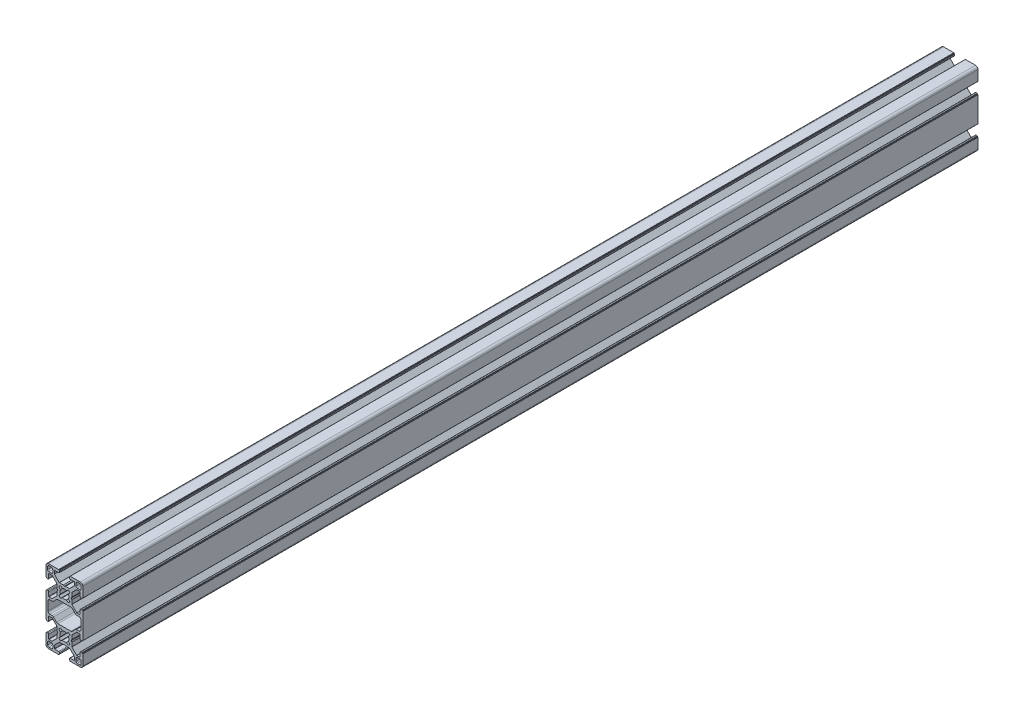
SolidWorks part; units mm, degrees
ref_plane "Front Plane" through (0, 0, 0) normal (0, 0, 1) x (1, 0, 0)
ref_plane "Top Plane" through (0, 0, 0) normal (0, 1, 0) x (1, 0, 0)
ref_plane "Right Plane" through (0, 0, 0) normal (1, 0, 0) x (0, 0, -1)
sketch "Sketch1" plane through (0, 0, 0) normal (0, 0, 1) x (1, 0, 0)
  line L0 (15.3348, -15) -> (-18.6959, -15) construction
  line L1 (-20.9994, 0) -> (26.1762, 0) construction
  line L2 (1.6001, -18.2806) -> (3.1547, -19.5053)
  line L3 (4.1172, -21) -> (0.9, -21)
  line L4 (4.35, -29.5) -> (4.25, -29.5)
  line L5 (4.05, -29.3) -> (4.05, -28.4)
  line L6 (4.55, -29.7) -> (4.55, -29.8)
  line L7 (0.9, -21) -> (0.1019, -20.5392)
  line L8 (1.6001, -11.7194) -> (3.1547, -10.4947)
  line L9 (3.2806, -13.3999) -> (4.5184, -11.8641)
  line L10 (3.2806, -16.6001) -> (4.5184, -18.1359)
  line L11 (6.0045, -19.1216) -> (6.0045, -15.9)
  line L12 (12.6, -23.25) -> (10.1328, -23.25)
  line L13 (10.5, -24.5) -> (12.7, -24.5)
  line L14 (12.7, -28.7) -> (10.5, -28.7)
  line L15 (15, -28) -> (15, -19.75)
  line L16 (13.7, -25.5) -> (13.7, -27.7)
  line L17 (14.8, -19.55) -> (14.7, -19.55)
  line L18 (14.5, -19.35) -> (14.5, -19.25)
  line L19 (14.3, -19.05) -> (13.4, -19.05)
  line L20 (12.8, -19.65) -> (12.8, -23.05)
  line L21 (8.25, -27.6) -> (8.25, -25.1328)
  line L22 (9.5, -27.7) -> (9.5, -25.5)
  line L23 (9.9914, -23.1914) -> (6.063, -19.263)
  line L24 (12.8, -10.35) -> (12.8, -6.95)
  line L25 (15, 10.25) -> (15, -10.25)
  line L26 (9.9914, -6.8086) -> (6.063, -10.737)
  line L27 (8.9272, -5.5393) -> (6.4104, -8.0562)
  line L28 (14.3, -10.95) -> (13.4, -10.95)
  line L29 (14.5, -10.65) -> (14.5, -10.75)
  line L30 (14.8, -10.45) -> (14.7, -10.45)
  line L31 (6.0045, -10.8784) -> (6.0045, -14.1)
  line L32 (6.0045, -15.9) -> (5.5426, -15.1)
  line L33 (6.0045, -14.1) -> (5.5426, -14.9)
  line L34 (12.6, -6.75) -> (10.1328, -6.75)
  line L35 (11.85, -5.1) -> (9.9879, -5.1)
  line L36 (13.35, 3.6) -> (13.35, -3.6)
  line L37 (4.75, -30) -> (13, -30)
  line L38 (8.1914, -24.9914) -> (4.2586, -21.0586)
  line L39 (4.65, -27.8) -> (8.05, -27.8)
  line L40 (-1.6001, 18.2806) -> (-3.1547, 19.5053)
  line L41 (-4.1172, 21) -> (-0.9, 21)
  line L42 (-4.35, 29.5) -> (-4.25, 29.5)
  line L43 (-4.05, 29.3) -> (-4.05, 28.4)
  line L44 (-4.55, 29.7) -> (-4.55, 29.8)
  line L45 (-0.9, 21) -> (-0.1019, 20.5392)
  line L46 (-1.6001, 11.7194) -> (-3.1547, 10.4947)
  line L47 (-5.3497, 8.4955) -> (5.3497, 8.4955)
  line L48 (-3.2806, 13.3999) -> (-4.5184, 11.8641)
  line L49 (-3.2806, 16.6001) -> (-4.5184, 18.1359)
  line L50 (-6.0045, 19.1216) -> (-6.0045, 15.9)
  line L51 (-12.6, 23.25) -> (-10.1328, 23.25)
  line L52 (-10.5, 24.5) -> (-12.7, 24.5)
  line L53 (-12.7, 28.7) -> (-10.5, 28.7)
  line L54 (-15, 28) -> (-15, 19.75)
  line L55 (-13.7, 25.5) -> (-13.7, 27.7)
  line L56 (-14.8, 19.55) -> (-14.7, 19.55)
  line L57 (-14.5, 19.35) -> (-14.5, 19.25)
  line L58 (-14.3, 19.05) -> (-13.4, 19.05)
  line L59 (-12.8, 19.65) -> (-12.8, 23.05)
  line L60 (-8.25, 27.6) -> (-8.25, 25.1328)
  line L61 (-9.5, 27.7) -> (-9.5, 25.5)
  line L62 (-9.9914, 23.1914) -> (-6.063, 19.263)
  line L63 (-12.8, 10.35) -> (-12.8, 6.95)
  line L64 (-9.9914, 6.8086) -> (-6.063, 10.737)
  line L65 (-8.9272, 5.5393) -> (-6.4104, 8.0562)
  line L66 (-14.3, 10.95) -> (-13.4, 10.95)
  line L67 (-14.5, 10.65) -> (-14.5, 10.75)
  line L68 (-14.8, 10.45) -> (-14.7, 10.45)
  line L69 (-6.0045, 10.8784) -> (-6.0045, 14.1)
  line L70 (-6.0045, 15.9) -> (-5.5426, 15.1)
  line L71 (-6.0045, 14.1) -> (-5.5426, 14.9)
  line L72 (-12.6, 6.75) -> (-10.1328, 6.75)
  line L73 (-11.85, 5.1) -> (-9.9879, 5.1)
  line L74 (-4.75, 30) -> (-13, 30)
  line L75 (-8.1914, 24.9914) -> (-4.2586, 21.0586)
  line L76 (-4.65, 27.8) -> (-8.05, 27.8)
  line L77 (4.65, 27.8) -> (8.05, 27.8)
  line L78 (8.1914, 24.9914) -> (4.2586, 21.0586)
  line L79 (4.75, 30) -> (13, 30)
  line L80 (11.85, 5.1) -> (9.9879, 5.1)
  line L81 (12.6, 6.75) -> (10.1328, 6.75)
  line L82 (6.0045, 14.1) -> (5.5426, 14.9)
  line L83 (6.0045, 15.9) -> (5.5426, 15.1)
  line L84 (6.0045, 10.8784) -> (6.0045, 14.1)
  line L85 (14.8, 10.45) -> (14.7, 10.45)
  line L86 (14.5, 10.65) -> (14.5, 10.75)
  line L87 (14.3, 10.95) -> (13.4, 10.95)
  line L88 (8.9272, 5.5393) -> (6.4104, 8.0562)
  line L89 (9.9914, 6.8086) -> (6.063, 10.737)
  line L90 (12.8, 10.35) -> (12.8, 6.95)
  line L91 (9.9914, 23.1914) -> (6.063, 19.263)
  line L92 (9.5, 27.7) -> (9.5, 25.5)
  line L93 (8.25, 27.6) -> (8.25, 25.1328)
  line L94 (12.8, 19.65) -> (12.8, 23.05)
  line L95 (14.3, 19.05) -> (13.4, 19.05)
  line L96 (14.5, 19.35) -> (14.5, 19.25)
  line L97 (14.8, 19.55) -> (14.7, 19.55)
  line L98 (13.7, 25.5) -> (13.7, 27.7)
  line L99 (15, 28) -> (15, 19.75)
  line L100 (12.7, 28.7) -> (10.5, 28.7)
  line L101 (10.5, 24.5) -> (12.7, 24.5)
  line L102 (12.6, 23.25) -> (10.1328, 23.25)
  line L103 (6.0045, 19.1216) -> (6.0045, 15.9)
  line L104 (3.2806, 16.6001) -> (4.5184, 18.1359)
  line L105 (3.2806, 13.3999) -> (4.5184, 11.8641)
  line L106 (1.6001, 11.7194) -> (3.1547, 10.4947)
  line L107 (0.9, 21) -> (0.1019, 20.5392)
  line L108 (4.55, 29.7) -> (4.55, 29.8)
  line L109 (4.05, 29.3) -> (4.05, 28.4)
  line L110 (4.35, 29.5) -> (4.25, 29.5)
  line L111 (4.1172, 21) -> (0.9, 21)
  line L112 (1.6001, 18.2806) -> (3.1547, 19.5053)
  line L155 (0, 26.7355) -> (0, -34.1789) construction
  line L156 (-4.65, -27.8) -> (-8.05, -27.8)
  line L157 (-8.1914, -24.9914) -> (-4.2586, -21.0586)
  line L158 (-4.75, -30) -> (-13, -30)
  line L162 (-13.35, 3.6) -> (-13.35, -3.6)
  line L163 (-11.85, -5.1) -> (-9.9879, -5.1)
  line L164 (-12.6, -6.75) -> (-10.1328, -6.75)
  line L165 (-6.0045, -14.1) -> (-5.5426, -14.9)
  line L166 (-6.0045, -15.9) -> (-5.5426, -15.1)
  line L167 (-6.0045, -10.8784) -> (-6.0045, -14.1)
  line L168 (-14.8, -10.45) -> (-14.7, -10.45)
  line L169 (-14.5, -10.65) -> (-14.5, -10.75)
  line L170 (-14.3, -10.95) -> (-13.4, -10.95)
  line L171 (-8.9272, -5.5393) -> (-6.4104, -8.0562)
  line L172 (-9.9914, -6.8086) -> (-6.063, -10.737)
  line L173 (-15, 10.25) -> (-15, -10.25)
  line L174 (-12.8, -10.35) -> (-12.8, -6.95)
  line L176 (-9.9914, -23.1914) -> (-6.063, -19.263)
  line L177 (-9.5, -27.7) -> (-9.5, -25.5)
  line L178 (-8.25, -27.6) -> (-8.25, -25.1328)
  line L179 (-12.8, -19.65) -> (-12.8, -23.05)
  line L180 (-14.3, -19.05) -> (-13.4, -19.05)
  line L181 (-14.5, -19.35) -> (-14.5, -19.25)
  line L182 (-14.8, -19.55) -> (-14.7, -19.55)
  line L183 (-13.7, -25.5) -> (-13.7, -27.7)
  line L184 (-15, -28) -> (-15, -19.75)
  line L185 (-12.7, -28.7) -> (-10.5, -28.7)
  line L186 (-10.5, -24.5) -> (-12.7, -24.5)
  line L187 (-12.6, -23.25) -> (-10.1328, -23.25)
  line L188 (-6.0045, -19.1216) -> (-6.0045, -15.9)
  line L214 (-3.2806, -16.6001) -> (-4.5184, -18.1359)
  line L215 (-3.2806, -13.3999) -> (-4.5184, -11.8641)
  line L216 (-5.3497, -8.4955) -> (5.3497, -8.4955)
  line L217 (-1.6001, -11.7194) -> (-3.1547, -10.4947)
  line L226 (-0.9, -21) -> (-0.1019, -20.5392)
  line L234 (-4.55, -29.7) -> (-4.55, -29.8)
  line L235 (-4.05, -29.3) -> (-4.05, -28.4)
  line L236 (-4.35, -29.5) -> (-4.25, -29.5)
  line L237 (-4.1172, -21) -> (-0.9, -21)
  line L238 (-1.6001, -18.2806) -> (-3.1547, -19.5053)
  arc A0 (4.5184, -18.1359) -> (3.1547, -19.5053) centre (0, -15) cw
  arc A1 (4.35, -29.5) -> (4.55, -29.7) centre (4.35, -29.7) cw
  arc A2 (4.25, -29.5) -> (4.05, -29.3) centre (4.25, -29.3) cw
  arc A3 (4.75, -30) -> (4.55, -29.8) centre (4.75, -29.8) cw
  arc A4 (4.05, -28.4) -> (4.65, -27.8) centre (4.65, -28.4) cw
  arc A5 (4.1172, -21) -> (4.2586, -21.0586) centre (4.1172, -21.2) cw
  arc A6 (3.2806, -13.3999) -> (3.2806, -16.6001) centre (0, -15) cw
  arc A7 (3.1547, -10.4947) -> (4.5184, -11.8641) centre (0, -15) cw
  arc A8 (12.6, -6.75) -> (12.8, -6.95) centre (12.6, -6.95) cw
  arc A9 (13.35, -3.6) -> (11.85, -5.1) centre (11.85, -3.6) cw
  arc A10 (9.9914, -6.8086) -> (10.1328, -6.75) centre (10.1328, -6.95) cw
  arc A11 (8.9272, -5.5393) -> (9.9879, -5.1) centre (9.9879, -6.6) cw
  arc A12 (15, -28) -> (13, -30) centre (13, -28) cw
  arc A13 (12.7, -24.5) -> (13.7, -25.5) centre (12.7, -25.5) cw
  arc A14 (13.7, -27.7) -> (12.7, -28.7) centre (12.7, -27.7) cw
  arc A15 (14.7, -19.55) -> (14.5, -19.35) centre (14.7, -19.35) cw
  arc A16 (14.8, -19.55) -> (15, -19.75) centre (14.8, -19.75) cw
  arc A17 (14.3, -19.05) -> (14.5, -19.25) centre (14.3, -19.25) cw
  arc A18 (12.8, -19.65) -> (13.4, -19.05) centre (13.4, -19.65) cw
  arc A19 (12.8, -23.05) -> (12.6, -23.25) centre (12.6, -23.05) cw
  arc A20 (9.5, -25.5) -> (10.5, -24.5) centre (10.5, -25.5) cw
  arc A21 (8.1914, -24.9914) -> (8.25, -25.1328) centre (8.05, -25.1328) cw
  arc A22 (8.25, -27.6) -> (8.05, -27.8) centre (8.05, -27.6) cw
  arc A23 (10.5, -28.7) -> (9.5, -27.7) centre (10.5, -27.7) cw
  arc A24 (10.1328, -23.25) -> (9.9914, -23.1914) centre (10.1328, -23.05) cw
  arc A25 (6.063, -19.263) -> (6.0045, -19.1216) centre (6.2045, -19.1216) cw
  arc A26 (14.5, -10.75) -> (14.3, -10.95) centre (14.3, -10.75) cw
  arc A27 (15, -10.25) -> (14.8, -10.45) centre (14.8, -10.25) cw
  arc A28 (14.5, -10.65) -> (14.7, -10.45) centre (14.7, -10.65) cw
  arc A29 (13.4, -10.95) -> (12.8, -10.35) centre (13.4, -10.35) cw
  arc A30 (5.5426, -15.1) -> (5.5426, -14.9) centre (5.7158, -15) cw
  arc A31 (6.0045, -10.8784) -> (6.063, -10.737) centre (6.2045, -10.8784) cw
  arc A32 (6.4104, -8.0562) -> (5.3497, -8.4955) centre (5.3497, -6.9955) cw
  arc A33 (-1.6001, 18.2806) -> (1.6001, 18.2806) centre (0, 15) cw
  arc A34 (1.6001, 11.7194) -> (-1.6001, 11.7194) centre (0, 15) cw
  arc A35 (-4.5184, 18.1359) -> (-3.1547, 19.5053) centre (0, 15) cw
  arc A36 (-4.35, 29.5) -> (-4.55, 29.7) centre (-4.35, 29.7) cw
  arc A37 (-4.25, 29.5) -> (-4.05, 29.3) centre (-4.25, 29.3) cw
  arc A38 (-4.75, 30) -> (-4.55, 29.8) centre (-4.75, 29.8) cw
  arc A39 (-4.05, 28.4) -> (-4.65, 27.8) centre (-4.65, 28.4) cw
  arc A40 (-4.1172, 21) -> (-4.2586, 21.0586) centre (-4.1172, 21.2) cw
  arc A41 (0.1019, 20.5392) -> (-0.1019, 20.5392) centre (0, 20.7158) cw
  arc A42 (-3.2806, 13.3999) -> (-3.2806, 16.6001) centre (0, 15) cw
  arc A43 (-3.1547, 10.4947) -> (-4.5184, 11.8641) centre (0, 15) cw
  arc A44 (-12.6, 6.75) -> (-12.8, 6.95) centre (-12.6, 6.95) cw
  arc A45 (-13.35, 3.6) -> (-11.85, 5.1) centre (-11.85, 3.6) cw
  arc A46 (-9.9914, 6.8086) -> (-10.1328, 6.75) centre (-10.1328, 6.95) cw
  arc A47 (-8.9272, 5.5393) -> (-9.9879, 5.1) centre (-9.9879, 6.6) cw
  arc A48 (-15, 28) -> (-13, 30) centre (-13, 28) cw
  arc A49 (-12.7, 24.5) -> (-13.7, 25.5) centre (-12.7, 25.5) cw
  arc A50 (-13.7, 27.7) -> (-12.7, 28.7) centre (-12.7, 27.7) cw
  arc A51 (-14.7, 19.55) -> (-14.5, 19.35) centre (-14.7, 19.35) cw
  arc A52 (-14.8, 19.55) -> (-15, 19.75) centre (-14.8, 19.75) cw
  arc A53 (-14.3, 19.05) -> (-14.5, 19.25) centre (-14.3, 19.25) cw
  arc A54 (-12.8, 19.65) -> (-13.4, 19.05) centre (-13.4, 19.65) cw
  arc A55 (-12.8, 23.05) -> (-12.6, 23.25) centre (-12.6, 23.05) cw
  arc A56 (-9.5, 25.5) -> (-10.5, 24.5) centre (-10.5, 25.5) cw
  arc A57 (-8.1914, 24.9914) -> (-8.25, 25.1328) centre (-8.05, 25.1328) cw
  arc A58 (-8.25, 27.6) -> (-8.05, 27.8) centre (-8.05, 27.6) cw
  arc A59 (-10.5, 28.7) -> (-9.5, 27.7) centre (-10.5, 27.7) cw
  arc A60 (-10.1328, 23.25) -> (-9.9914, 23.1914) centre (-10.1328, 23.05) cw
  arc A61 (-6.063, 19.263) -> (-6.0045, 19.1216) centre (-6.2045, 19.1216) cw
  arc A62 (-14.5, 10.75) -> (-14.3, 10.95) centre (-14.3, 10.75) cw
  arc A63 (-15, 10.25) -> (-14.8, 10.45) centre (-14.8, 10.25) cw
  arc A64 (-14.5, 10.65) -> (-14.7, 10.45) centre (-14.7, 10.65) cw
  arc A65 (-13.4, 10.95) -> (-12.8, 10.35) centre (-13.4, 10.35) cw
  arc A66 (-5.5426, 15.1) -> (-5.5426, 14.9) centre (-5.7158, 15) cw
  arc A67 (-6.0045, 10.8784) -> (-6.063, 10.737) centre (-6.2045, 10.8784) cw
  arc A68 (-6.4104, 8.0562) -> (-5.3497, 8.4955) centre (-5.3497, 6.9955) cw
  arc A69 (6.4104, 8.0562) -> (5.3497, 8.4955) centre (5.3497, 6.9955) ccw
  arc A70 (6.0045, 10.8784) -> (6.063, 10.737) centre (6.2045, 10.8784) ccw
  arc A71 (5.5426, 15.1) -> (5.5426, 14.9) centre (5.7158, 15) ccw
  arc A72 (13.4, 10.95) -> (12.8, 10.35) centre (13.4, 10.35) ccw
  arc A73 (14.5, 10.65) -> (14.7, 10.45) centre (14.7, 10.65) ccw
  arc A74 (15, 10.25) -> (14.8, 10.45) centre (14.8, 10.25) ccw
  arc A75 (14.5, 10.75) -> (14.3, 10.95) centre (14.3, 10.75) ccw
  arc A76 (6.063, 19.263) -> (6.0045, 19.1216) centre (6.2045, 19.1216) ccw
  arc A77 (10.1328, 23.25) -> (9.9914, 23.1914) centre (10.1328, 23.05) ccw
  arc A78 (10.5, 28.7) -> (9.5, 27.7) centre (10.5, 27.7) ccw
  arc A79 (8.25, 27.6) -> (8.05, 27.8) centre (8.05, 27.6) ccw
  arc A80 (8.1914, 24.9914) -> (8.25, 25.1328) centre (8.05, 25.1328) ccw
  arc A81 (9.5, 25.5) -> (10.5, 24.5) centre (10.5, 25.5) ccw
  arc A82 (12.8, 23.05) -> (12.6, 23.25) centre (12.6, 23.05) ccw
  arc A83 (12.8, 19.65) -> (13.4, 19.05) centre (13.4, 19.65) ccw
  arc A84 (14.3, 19.05) -> (14.5, 19.25) centre (14.3, 19.25) ccw
  arc A85 (14.8, 19.55) -> (15, 19.75) centre (14.8, 19.75) ccw
  arc A86 (14.7, 19.55) -> (14.5, 19.35) centre (14.7, 19.35) ccw
  arc A87 (13.7, 27.7) -> (12.7, 28.7) centre (12.7, 27.7) ccw
  arc A88 (12.7, 24.5) -> (13.7, 25.5) centre (12.7, 25.5) ccw
  arc A89 (15, 28) -> (13, 30) centre (13, 28) ccw
  arc A90 (8.9272, 5.5393) -> (9.9879, 5.1) centre (9.9879, 6.6) ccw
  arc A91 (9.9914, 6.8086) -> (10.1328, 6.75) centre (10.1328, 6.95) ccw
  arc A92 (13.35, 3.6) -> (11.85, 5.1) centre (11.85, 3.6) ccw
  arc A93 (12.6, 6.75) -> (12.8, 6.95) centre (12.6, 6.95) ccw
  arc A94 (3.1547, 10.4947) -> (4.5184, 11.8641) centre (0, 15) ccw
  arc A95 (3.2806, 13.3999) -> (3.2806, 16.6001) centre (0, 15) ccw
  arc A96 (4.1172, 21) -> (4.2586, 21.0586) centre (4.1172, 21.2) ccw
  arc A97 (4.05, 28.4) -> (4.65, 27.8) centre (4.65, 28.4) ccw
  arc A98 (4.75, 30) -> (4.55, 29.8) centre (4.75, 29.8) ccw
  arc A99 (4.25, 29.5) -> (4.05, 29.3) centre (4.25, 29.3) ccw
  arc A100 (4.35, 29.5) -> (4.55, 29.7) centre (4.35, 29.7) ccw
  arc A101 (4.5184, 18.1359) -> (3.1547, 19.5053) centre (0, 15) ccw
  arc A138 (-6.4104, -8.0562) -> (-5.3497, -8.4955) centre (-5.3497, -6.9955) ccw
  arc A140 (-6.0045, -10.8784) -> (-6.063, -10.737) centre (-6.2045, -10.8784) ccw
  arc A141 (-5.5426, -15.1) -> (-5.5426, -14.9) centre (-5.7158, -15) ccw
  arc A142 (-13.4, -10.95) -> (-12.8, -10.35) centre (-13.4, -10.35) ccw
  arc A143 (-14.5, -10.65) -> (-14.7, -10.45) centre (-14.7, -10.65) ccw
  arc A144 (-15, -10.25) -> (-14.8, -10.45) centre (-14.8, -10.25) ccw
  arc A145 (-14.5, -10.75) -> (-14.3, -10.95) centre (-14.3, -10.75) ccw
  arc A147 (-6.063, -19.263) -> (-6.0045, -19.1216) centre (-6.2045, -19.1216) ccw
  arc A148 (-10.1328, -23.25) -> (-9.9914, -23.1914) centre (-10.1328, -23.05) ccw
  arc A149 (-10.5, -28.7) -> (-9.5, -27.7) centre (-10.5, -27.7) ccw
  arc A150 (-8.25, -27.6) -> (-8.05, -27.8) centre (-8.05, -27.6) ccw
  arc A151 (-8.1914, -24.9914) -> (-8.25, -25.1328) centre (-8.05, -25.1328) ccw
  arc A152 (-9.5, -25.5) -> (-10.5, -24.5) centre (-10.5, -25.5) ccw
  arc A153 (-12.8, -23.05) -> (-12.6, -23.25) centre (-12.6, -23.05) ccw
  arc A154 (-12.8, -19.65) -> (-13.4, -19.05) centre (-13.4, -19.65) ccw
  arc A155 (-14.3, -19.05) -> (-14.5, -19.25) centre (-14.3, -19.25) ccw
  arc A156 (-14.8, -19.55) -> (-15, -19.75) centre (-14.8, -19.75) ccw
  arc A157 (-14.7, -19.55) -> (-14.5, -19.35) centre (-14.7, -19.35) ccw
  arc A158 (-13.7, -27.7) -> (-12.7, -28.7) centre (-12.7, -27.7) ccw
  arc A159 (-12.7, -24.5) -> (-13.7, -25.5) centre (-12.7, -25.5) ccw
  arc A160 (-15, -28) -> (-13, -30) centre (-13, -28) ccw
  arc A184 (-8.9272, -5.5393) -> (-9.9879, -5.1) centre (-9.9879, -6.6) ccw
  arc A185 (-9.9914, -6.8086) -> (-10.1328, -6.75) centre (-10.1328, -6.95) ccw
  arc A186 (-13.35, -3.6) -> (-11.85, -5.1) centre (-11.85, -3.6) ccw
  arc A187 (-12.6, -6.75) -> (-12.8, -6.95) centre (-12.6, -6.95) ccw
  arc A188 (-3.1547, -10.4947) -> (-4.5184, -11.8641) centre (0, -15) ccw
  arc A189 (-3.2806, -13.3999) -> (-3.2806, -16.6001) centre (0, -15) ccw
  arc A198 (0.1019, -20.5392) -> (-0.1019, -20.5392) centre (0, -20.7158) ccw
  arc A203 (-4.1172, -21) -> (-4.2586, -21.0586) centre (-4.1172, -21.2) ccw
  arc A204 (-4.05, -28.4) -> (-4.65, -27.8) centre (-4.65, -28.4) ccw
  arc A205 (-4.75, -30) -> (-4.55, -29.8) centre (-4.75, -29.8) ccw
  arc A206 (-4.25, -29.5) -> (-4.05, -29.3) centre (-4.25, -29.3) ccw
  arc A207 (-4.35, -29.5) -> (-4.55, -29.7) centre (-4.35, -29.7) ccw
  arc A208 (-4.5184, -18.1359) -> (-3.1547, -19.5053) centre (0, -15) ccw
  arc A261 (1.6001, -11.7194) -> (-1.6001, -11.7194) centre (0, -15) ccw
  arc A263 (-1.6001, -18.2806) -> (1.6001, -18.2806) centre (0, -15) ccw
  point P178 (0, -8.4955)
  point P382 (0, 8.4955)
  point P385 (-15, 0)
  point P387 (-13.35, 0)
  point P388 (13.35, 0)
  point P390 (15, 0)
  dimension "D7" = 7.3
  dimension "D9" = 11
  dimension "D1" = 30
  dimension "D2" = 60
  dimension "D3" = 8.1
  dimension "D4" = 9
  dimension "D5" = 30
  dimension "D6" = 8.1
  dimension "D8" = 15
  dimension "D10" = 16.5
  dimension "D11" = 16.5
extrude "Extrude1" add sketch "Sketch1" along normal blind 728.95
